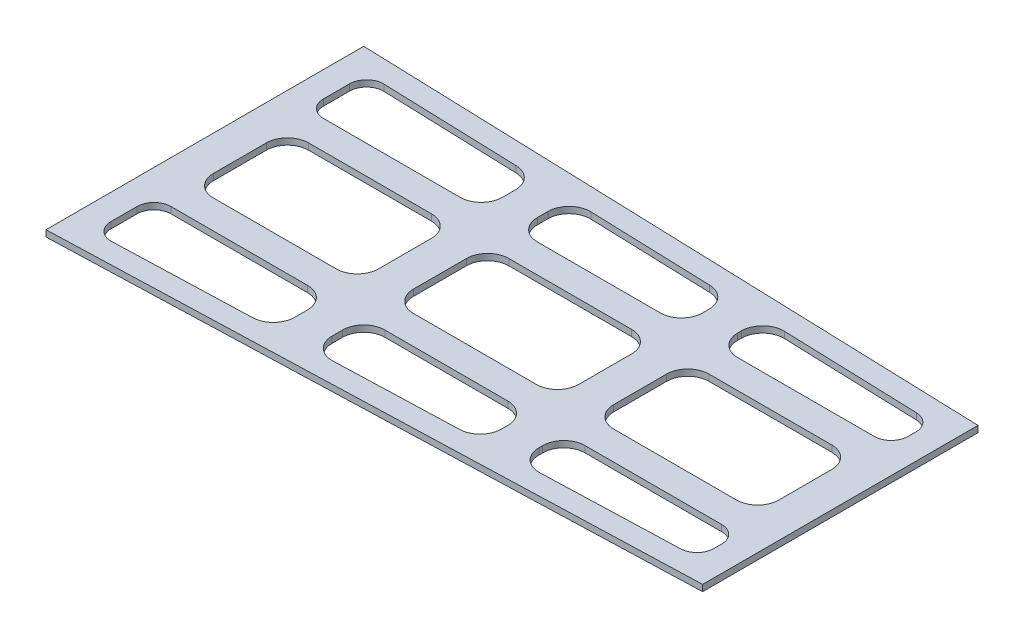
SolidWorks part; units mm, degrees
ref_plane "Front Plane" through (0, 0, 0) normal (0, 0, 1) x (1, 0, 0)
ref_plane "Top Plane" through (0, 0, 0) normal (0, 1, 0) x (1, 0, 0)
ref_plane "Right Plane" through (0, 0, 0) normal (1, 0, 0) x (0, 0, -1)
sketch "Sketch1" plane through (0, 0, 0) normal (0, 1, 0) x (1, 0, 0)
  line L0 (0, 0) -> (0, 75)
  line L7 (0, 75) -> (300, 65)
  line L8 (300, 65) -> (300, 0)
  line L9 (300, 0) -> (0, 0)
  point P0 (0, 0)
  dimension "D4" = 300
  dimension "D5" = 75
  dimension "D6" = 65
extrude "Boss-Extrude1" add sketch "Sketch1" along normal blind 3
mirror "Mirror1" of "Boss-Extrude1"
sketch "Sketch2" plane through (0, 3, 0) normal (0, 1, 0) x (1, 0, 0)
  line L0 (0, -1.65) -> (0, 1.65) construction
  line L1 (0, 31) -> (300, 31) construction
  line L2 (0, 31) -> (0, -31) construction
  line L3 (0, -31) -> (300, -31) construction
  line L4 (300, 31) -> (300, -31) construction
  line L5 (300, -65) -> (300, 65) construction
  line L6 (-1.65, 0) -> (1.65, 0) construction
  line L7 (55.5, 0) -> (150, 0) construction
  line L8 (94.5, -22.5) -> (16.5, -22.5)
  line L9 (94.5, -22.5) -> (94.5, 22.5)
  line L10 (94.5, 22.5) -> (16.5, 22.5)
  line L11 (16.5, -22.5) -> (16.5, 22.5)
  line L12 (94.5, -22.5) -> (16.5, 22.5) construction
  line L13 (94.5, 22.5) -> (16.5, -22.5) construction
  line L14 (189, -22.5) -> (111, -22.5)
  line L15 (189, -22.5) -> (189, 22.5)
  line L16 (189, 22.5) -> (111, 22.5)
  line L17 (111, -22.5) -> (111, 22.5)
  line L18 (189, -22.5) -> (111, 22.5) construction
  line L19 (189, 22.5) -> (111, -22.5) construction
  line L20 (283.5, -22.5) -> (205.5, -22.5)
  line L21 (283.5, -22.5) -> (283.5, 22.5)
  line L22 (283.5, 22.5) -> (205.5, 22.5)
  line L23 (205.5, -22.5) -> (205.5, 22.5)
  line L24 (283.5, -22.5) -> (205.5, 22.5) construction
  line L25 (283.5, 22.5) -> (205.5, -22.5) construction
  line L26 (150, 0) -> (244.5, 0) construction
  line L27 (0, 0) -> (55.5, 0) construction
  line L28 (244.5, 0) -> (300, 0) construction
  line L29 (16.5, -22.5) -> (0, -22.5) construction
  line L30 (94.5, -22.5) -> (111, -22.5) construction
  point P8 (0, 0)
  point P11 (55.5, 0)
  point P16 (150, 0)
  point P21 (244.5, 0)
  dimension "D1" = 62
  dimension "D2" = 45
  dimension "D3" = 78
extrude "Cut-Extrude1" cut sketch "Sketch2" against normal blind 10
fillet "Fillet1" radius 10 12 edges at (283.5, 1.5, 22.5) (94.5, 1.5, 22.5) (189, 1.5, 22.5) (94.5, 1.5, -22.5) (189, 1.5, -22.5) (283.5, 1.5, -22.5) (205.5, 1.5, 22.5) (111, 1.5, 22.5) (16.5, 1.5, 22.5) (16.5, 1.5, -22.5) (111, 1.5, -22.5) (205.5, 1.5, -22.5)
sketch "Sketch3" plane through (0, 3, 0) normal (0, 1, 0) x (1, 0, 0)
  line L0 (-1.65, 0) -> (1.65, 0) construction
  line L1 (-87.6274, -30) -> (294.5978, -30) construction
  line L2 (-87.6274, -30) -> (-87.6274, 30) construction
  line L3 (-87.6274, 30) -> (294.5978, 30) construction
  line L4 (294.5978, -30) -> (294.5978, 30) construction
  line L5 (-87.6274, -30) -> (294.5978, 30) construction
  line L6 (-87.6274, 30) -> (294.5978, -30) construction
  line L7 (12, 56.3233) -> (12, 44)
  line L8 (20, 36) -> (280, 36)
  line L9 (288, 44) -> (288, 47.6567)
  line L10 (280.2665, 55.6522) -> (20.2665, 64.3189)
  line L11 (0, -1.65) -> (0, 1.65) construction
  line L12 (300, -65) -> (300, 65) construction
  line L13 (300, 65) -> (0, 75) construction
  arc A0 (288, 47.6567) -> (280.2665, 55.6522) centre (280, 47.6567) ccw
  arc A1 (280, 36) -> (288, 44) centre (280, 44) ccw
  arc A2 (12, 44) -> (20, 36) centre (20, 44) ccw
  arc A3 (12, 56.3233) -> (20.2665, 64.3189) centre (20, 56.3233) cw
  point P0 (103.4852, 0)
  dimension "D6" = 8
  dimension "D1" = 60
  dimension "D2" = 12
  dimension "D3" = 12
  dimension "D4" = 10
  dimension "D5" = 6
extrude "Cut-Extrude2" cut sketch "Sketch3" against normal blind 10
mirror "Mirror2" about plane through (0, 0, 0) normal (0, 0, 1) of "Cut-Extrude2"
sketch "Sketch4" plane through (0, 3, 0) normal (0, 1, 0) x (1, 0, 0)
  line L0 (-1.65, 0) -> (1.65, 0) construction
  line L1 (94.5, -67.4177) -> (111, -67.4177)
  line L2 (94.5, -67.4177) -> (94.5, 67.4177)
  line L3 (94.5, 67.4177) -> (111, 67.4177)
  line L4 (111, -67.4177) -> (111, 67.4177)
  line L5 (94.5, -67.4177) -> (111, 67.4177) construction
  line L6 (94.5, 67.4177) -> (111, -67.4177) construction
  line L7 (111, 12.5) -> (111, -12.5) construction
  line L8 (94.5, -12.5) -> (94.5, 12.5) construction
  line L9 (205.5, 12.5) -> (205.5, -12.5) construction
  line L10 (189, -63.0534) -> (205.5, -63.0534)
  line L11 (189, -63.0534) -> (189, 63.0534)
  line L12 (189, 63.0534) -> (205.5, 63.0534)
  line L13 (205.5, -63.0534) -> (205.5, 63.0534)
  line L14 (189, -63.0534) -> (205.5, 63.0534) construction
  line L15 (189, 63.0534) -> (205.5, -63.0534) construction
  line L16 (189, -12.5) -> (189, 12.5) construction
  point P0 (102.75, 0)
  point P11 (197.25, 0)
extrude "Boss-Extrude2" add sketch "Sketch4" against normal blind 3
fillet "Fillet2" radius 10 8 edges at (205.5, 1.5, -58.1444) (205.5, 1.5, -36) (189, 1.5, -58.6944) (189, 1.5, -36) (111, 1.5, -61.2944) (111, 1.5, -36) (94.5, 1.5, -36) (94.5, 1.5, -61.8444)
fillet "Fillet3" radius 10 8 edges at (189, 1.5, 58.6944) (94.5, 1.5, 61.8444) (94.5, 1.5, 36) (189, 1.5, 36) (111, 1.5, 61.2944) (205.5, 1.5, 58.1444) (111, 1.5, 36) (205.5, 1.5, 36)
